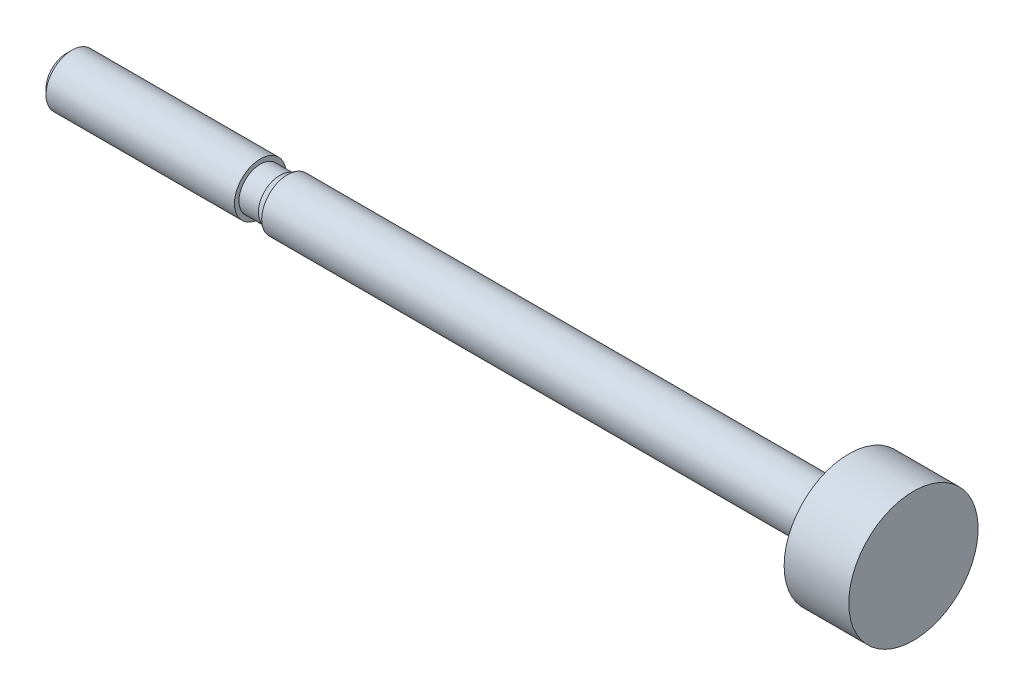
SolidWorks part; units mm, degrees
material "6061 合金"
ref_plane "前视基准面" through (0, 0, 0) normal (0, 0, 1) x (1, 0, 0)
ref_plane "上视基准面" through (0, 0, 0) normal (0, 1, 0) x (1, 0, 0)
ref_plane "右视基准面" through (0, 0, 0) normal (1, 0, 0) x (0, 0, -1)
ref_plane "基准面1" through (0, 0, 0) normal (0, 0, 1) x (1, 0, 0)
sketch "草图1" plane through (0, 0, 0) normal (0, 0, 1) x (1, 0, 0)
  line L0 (0, 0) -> (0, 1.5705)
  line L1 (0, 1.5705) -> (0.4295, 2)
  line L2 (0.4295, 2) -> (15, 2)
  line L3 (15, 2) -> (15, 1.65)
  line L4 (15, 1.65) -> (16.5, 1.65)
  line L5 (16.5, 1.65) -> (17.1062, 2)
  line L6 (17.1062, 2) -> (60.5, 2)
  line L7 (60.5, 2) -> (60.5, 5)
  line L8 (60.5, 5) -> (65.5, 5)
  line L9 (65.5, 5) -> (65.5, 0)
  line L10 (65.5, 0) -> (0, 0)
  line L11 (65.5, 0) -> (0, 0) construction
revolve "旋转1" add sketch "草图1" angle 360 about L11
cosmetic thread "装饰螺纹线1" parameters "D1"=15, "D2"=3.141
move or copy body "实体-移动/复制1" [suppressed] bodies to move or copy 106
